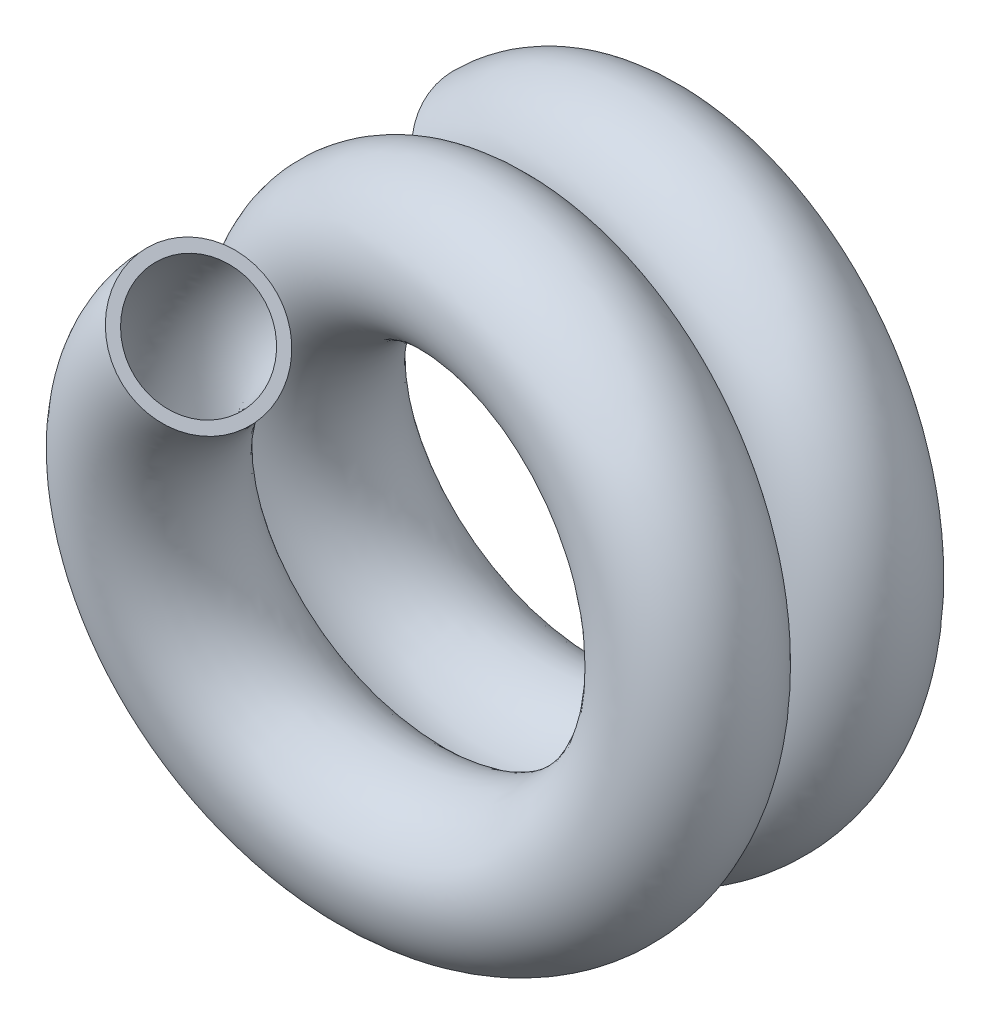
SolidWorks part; units mm, degrees
ref_plane "Front Plane" through (0, 0, 0) normal (0, 0, 1) x (1, 0, 0)
ref_plane "Top Plane" through (0, 0, 0) normal (0, 1, 0) x (1, 0, 0)
ref_plane "Right Plane" through (0, 0, 0) normal (1, 0, 0) x (0, 0, -1)
sketch "Sketch1" plane through (0, 0, 0) normal (0, 0, 1) x (1, 0, 0)
  circle A0 centre (0, 0) radius 76.2
  dimension "D1" = 152.4
curve "Helix/Spiral2" pitch 50.8 height 101.6 turns 2
ref_plane "Plane1" through (-53.8815, 53.8815, 0) normal (0.7032, 0.7032, 0.1055) x (0.7098, -0.6855, -0.1621)
sketch "Sketch3" plane through (-53.8815, 53.8815, 0) normal (0.7032, 0.7032, 0.1055) x (0.7098, -0.6855, -0.1621)
  circle A0 centre (0, 0) radius 24.13
  circle A1 centre (0, 0) radius 20.193
  dimension "D1" = 48.26
  dimension "D2" = 40.386
sweep "Sweep1" add profiles "Sketch3" path "Helix/Spiral2"
equation "\"Foamcore\" = .1in"
equation "\"MDF\" = .2in"
equation "\"Gmaterial\"= \"MDF\""
equation "\"PVC-ID\" = \"1.590in\""
equation "\"PVC-OD\" = \"1.900in\""
equation "\"D1@Sketch3\"=\"PVC-OD\""
equation "\"D2@Sketch3\"=\"PVC-ID\""
